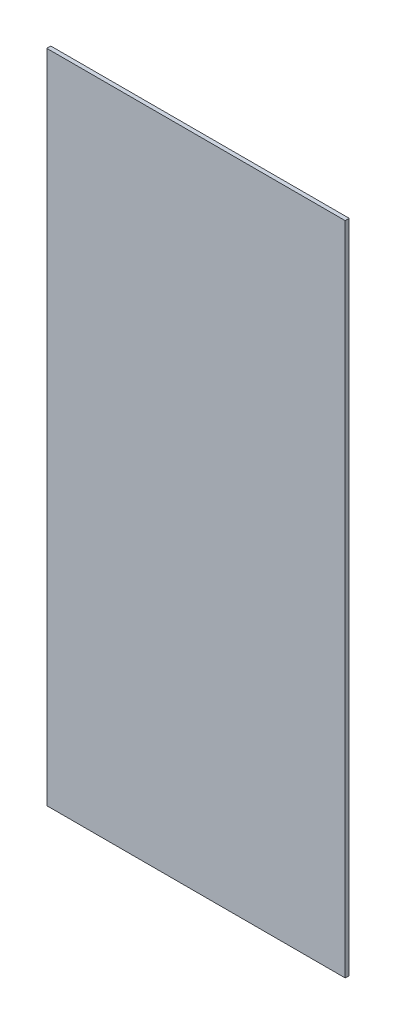
SolidWorks part; units mm, degrees
material "Acrylic (Medium-high impact)"
ref_plane "Front Plane" through (0, 0, 0) normal (0, 0, 1) x (1, 0, 0)
ref_plane "Top Plane" through (0, 0, 0) normal (0, 1, 0) x (1, 0, 0)
ref_plane "Right Plane" through (0, 0, 0) normal (1, 0, 0) x (0, 0, -1)
sketch "Sketch1" plane through (0, 0, 0) normal (0, 0, 1) x (1, 0, 0)
  line L1 (-114.3, 251.1933) -> (114.3, 251.1933)
  line L2 (-114.3, 251.1933) -> (-114.3, -251.1933)
  line L3 (-114.3, -251.1933) -> (114.3, -251.1933)
  line L4 (114.3, 251.1933) -> (114.3, -251.1933)
  line L5 (-114.3, 251.1933) -> (114.3, -251.1933) construction
  line L6 (-114.3, -251.1933) -> (114.3, 251.1933) construction
  point P0 (0, 0)
  dimension "D1" = 228.6
  dimension "D2" = 502.3866
extrude "Boss-Extrude1" add sketch "Sketch1" along normal blind 3.0734
equation "\"Height\"= 32in"
equation "\"Width\"= 23in"
equation "\"Depth\"= 20in"
equation "\"Plexi\"= .121in"
equation "\"EBWidth\" = 9in"
equation "\"MagnetThickness\"=3mm"
equation "\"MagnetDiameter\"=12mm"
equation "\"DoorPlexi\" = \"Plexi\""
equation "\"BasePlateThickness\" = 0.5in"
equation "\"BasePlateWidth\" = \"Width\"+\"EBWidth\"-2*\"Plexi\""
equation "\"BasePlateDepth\" = \"Depth\"-\"Plexi\"-\"DoorPlexi\""
equation "\"Boxsize\" = .75in"
equation "\"BoxsizeHalf\" = \"Boxsize\"/2"
equation "\"Boxinner\" = .625in"
equation "\"CornerCube\" = 0.75in"
equation "\"FingerLength\" = 1.125in"
equation "\"FingerWidth\" = .625in"
equation "\"Cutwidth\"= .016in"
equation "\"Earsize\"= 1in + \"Cutwidth\" /2"
equation "\"Slotsize\" = 1in - \"CutWidth\" / 2"
equation "\"InnerWidth\" = \"Width\" - 2* \"Plexi\""
equation "\"InnerHeight\" = \"Height\" -2 * \"Plexi\""
equation "\"InnerDepth\" = \"Depth\" - 2*\"Plexi\""
equation "\"RearNumHoles\" = 7"
equation "\"RearHolesBorder\" = 2.2"
equation "\"RearHoleSpacing\" = (\"Width\" - 2*\"RearHolesBorder\") / (\"RearNumHoles\"-1)"
equation "\"RearBarLength\" = (\"InnerWidth\"-2*\"CornerCube\")"
equation "\"RearTopNumHoles\" = 6"
equation "\"RearTopHolesBorder\" = 2.5"
equation "\"RearTopHolesSpacing\" = (\"Width\" - 2*\"RearTopHolesBorder\") / (\"RearTopNumHoles\"-1)"
equation "\"SideTopNumHoles\" = 5"
equation "\"SideTopHoleOffset\"=\"CornerCube\"+\"FingerLength\"+\"Plexi\"+.5"
equation "\"SideHorizNumHoles\" = 6"
equation "\"SideHorizHoleBorder\" = 2.25"
equation "\"SideVertBarLength\"=\"Height\"-\"BasePlateThickness\"-2*\"CornerCube\"-\"Plexi\""
equation "\"SideVertNumHoles\" = 6"
equation "\"SideVertHolesBorder\" = \"CornerCube\"+\"FingerLength\"+.9"
equation "\"SideVertHoleSpacing\" = (\"InnerHeight\" - 2*\"SideVertHolesBorder\") / (\"SideVertNumHoles\"-1)"
equation "\"RearSideVertNumHoles\" = 7"
equation "\"RearSideVertHolesBorder\" = 2.5"
equation "\"RearSideVertHoleSpacing\" = (\"InnerHeight\" - 2*\"RearSideVertHolesBorder\") / (\"RearSideVertNumHoles\"-1)"
equation "\"RivetDia\" = .228in"
equation "\"SlotDepth\" = \"Plexi\" + 0.75in + .005in"
equation "\"SideSlotWidth\"   = \"Plexi\"+.005in"
equation "\"SidePanelVertSpacing\" = (\"Height\"-2*(1.75-\"Plexi\")) / 5"
equation "\"BottomPanelSideHoleSpacing\" = (\"InnerDepth\"-2*(1.75-\"Plexi\")) / 4"
equation "\"FrontDoorGap\" = .1in"
equation "\"TopDepth\" = \"Depth\"-\"DoorPlexi\"-\"FrontDoorGap\""
equation "\"TopBarDepth\" = \"Depth\"-\"DoorPlexi\"-\"Plexi\"-2*\"MagnetThickness\"-2*\"CornerCube\""
equation "\"CoolerDepth\" = 12in"
equation "\"ShelfGap\" = 0.5in"
equation "\"ShelfDepth\" = \"TopBarDepth\"+\"CornerCube\"-\"CoolerDepth\""
equation "\"ShelfBarDepth\"=\"ShelfDepth\"-2*\"CornerCube\""
equation "\"ShelfWidth\" = \"EBWidth\"-\"ShelfGap\""
equation "\"ShelfBarWidth\" = \"EBWidth\"-\"Boxsize\""
equation "\"ShelfBarWidthShort\" = \"ShelfBarWidth\"-\"Boxsize\"-\"ShelfGap\""
equation "\"IntakeWidth\"=4in"
equation "\"IntakeHeight\"=2in"
equation "\"ExhaustWidth\"=4in"
equation "\"ExhaustHeight\"=2in"
equation "\"VentSpacing\"=7in"
equation "\"AngleBracketLength\"=20mm"
equation "\"AngleBracketWidth\"=.5in"
equation "\"AngleBracketThickness\"=.125in"
equation "\"AngleBracketHolePos\"=15mm"
equation "\"AngleBracketHoleDia\"=\"Rivet3_16Dia\""
equation "\"ShelfBarAngleHole\"=\"ShelfGap\"+\"Boxsize\"+\"AngleBracketHolePosShort\""
equation "\"D1@Sketch1\"=\"EBWidth\""
equation "\"D2@Sketch1\"=\"TopDepth\""
equation "\"D1@Boss-Extrude1\"=\"Plexi\""
